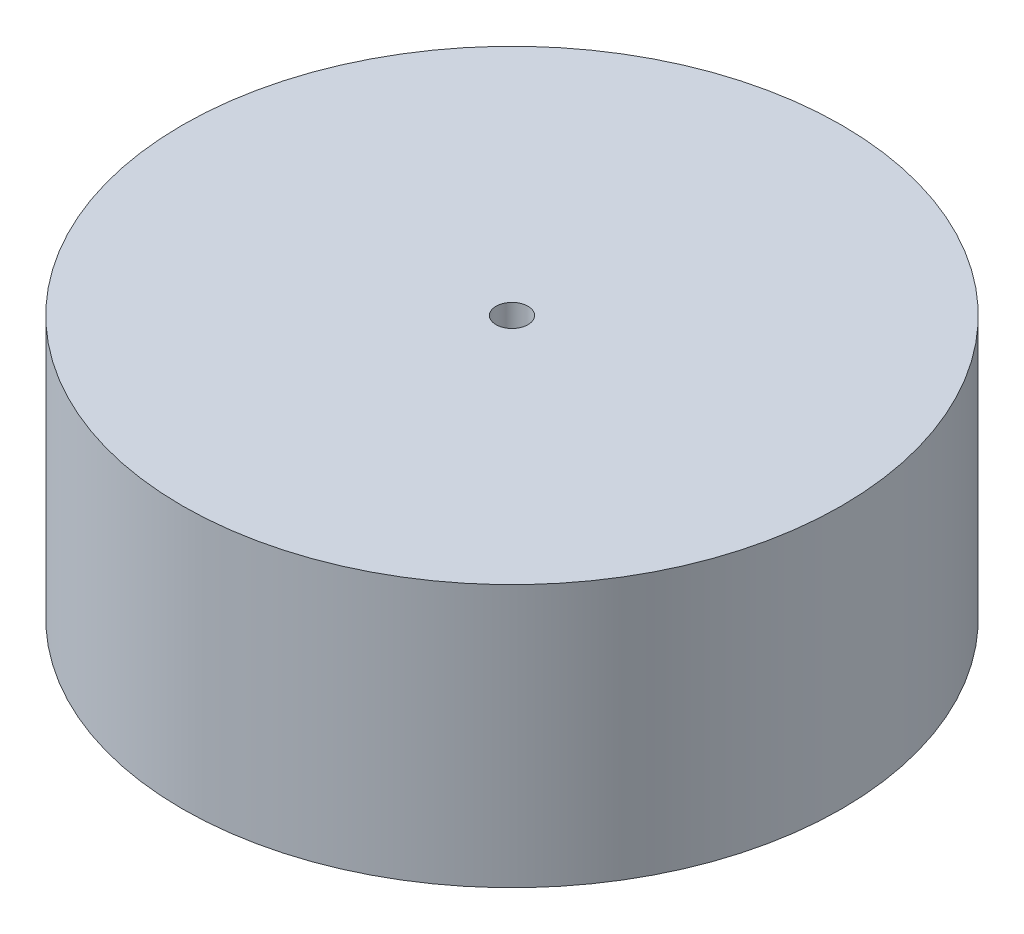
SolidWorks part; units mm, degrees
ref_plane "前视基准面" through (0, 0, 0) normal (0, 0, 1) x (1, 0, 0)
ref_plane "上视基准面" through (0, 0, 0) normal (0, 1, 0) x (1, 0, 0)
ref_plane "右视基准面" through (0, 0, 0) normal (1, 0, 0) x (0, 0, -1)
other "Configuration Table"
sketch "草图1" plane through (0, 0, 0) normal (0, 1, 0) x (1, 0, 0)
  circle A0 centre (0, 0) radius 51.5
  dimension "D1" = 103
extrude "凸台-拉伸1" add sketch "草图1" along normal blind 41
sketch "草图2" plane through (0, 41, 0) normal (0, 1, 0) x (1, 0, 0)
  circle A0 centre (0, 0) radius 2.5
extrude "切除-拉伸1" cut sketch "草图2" against normal through all
